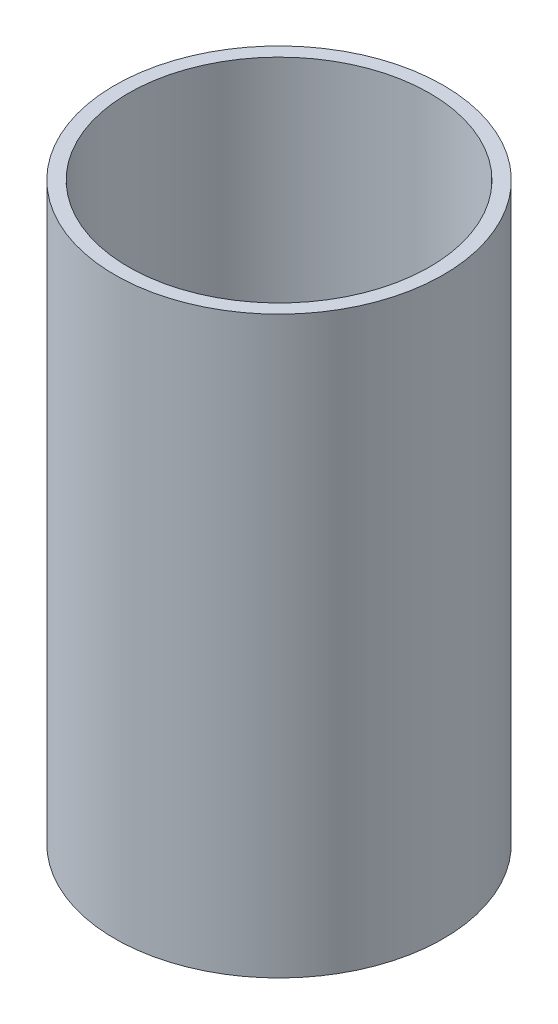
SolidWorks part; units mm, degrees
ref_plane "Front Plane" through (0, 0, 0) normal (1, 0, 0) x (0, 1, 0)
ref_plane "Top Plane" through (0, 0, 0) normal (0, 0, 1) x (0, 1, 0)
ref_plane "Right Plane" through (0, 0, 0) normal (0, 1, 0) x (-1, 0, 0)
sketch "Sketch1" plane through (0, 0, 0) normal (0, 1, 0) x (-1, 0, 0)
  circle A0 centre (0, 0) radius 11
  circle A1 centre (0, 0) radius 12
  dimension "D1" = 22
  dimension "D2" = 24
extrude "Boss-Extrude1" add sketch "Sketch1" along normal mid plane 42
